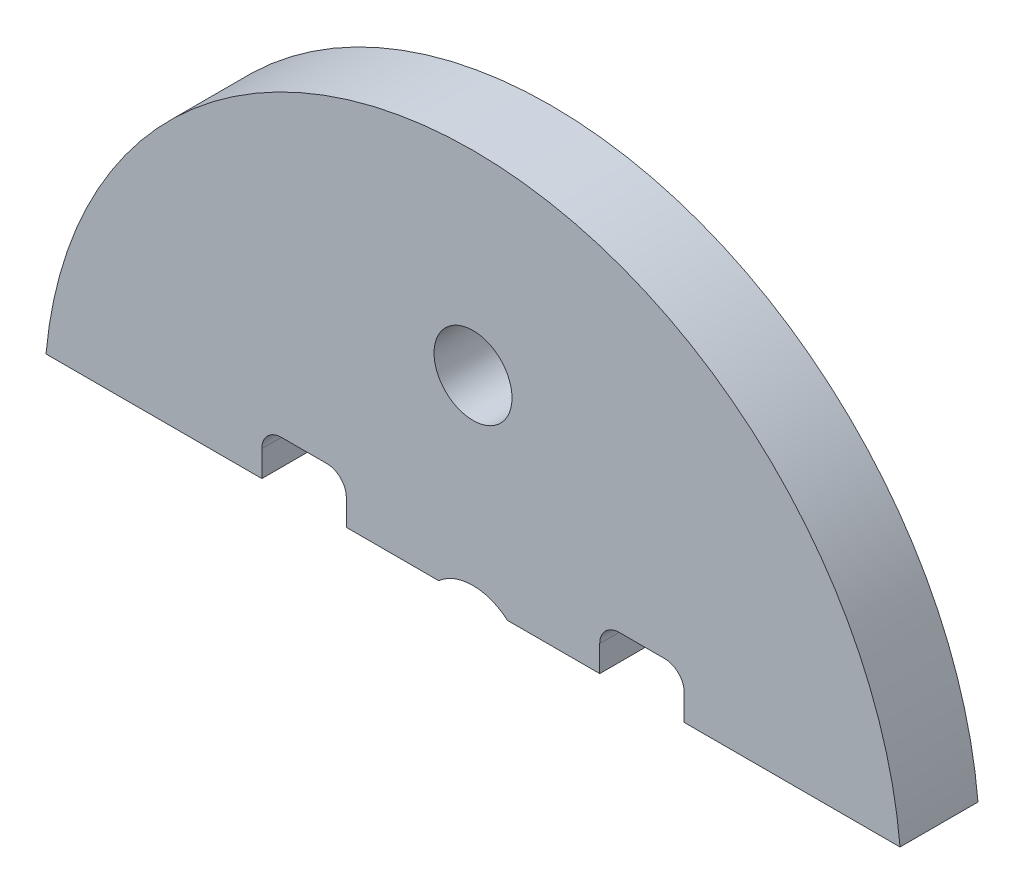
SolidWorks part; units mm, degrees
ref_plane "Alzado" through (0, 0, 0) normal (0, 0, 1) x (1, 0, 0)
ref_plane "Planta" through (0, 0, 0) normal (0, 1, 0) x (1, 0, 0)
ref_plane "Vista lateral" through (0, 0, 0) normal (1, 0, 0) x (0, 0, -1)
sketch "Model" plane through (0, 0, 0) normal (0, 0, 1) x (1, 0, 0)
  line L0 (223.1228, 245.202) -> (221.3728, 245.202)
  line L1 (208.3728, 245.202) -> (210.1228, 245.202)
  line L2 (223.8728, 243.452) -> (232.1795, 243.452)
  line L3 (223.8728, 243.452) -> (223.8728, 244.452)
  line L4 (220.6228, 244.452) -> (220.6228, 243.452)
  line L5 (210.8728, 244.452) -> (210.8728, 243.452)
  line L6 (207.6228, 243.452) -> (207.6228, 244.452)
  line L7 (199.3161, 243.452) -> (207.6228, 243.452)
  line L8 (210.8728, 243.452) -> (214.4249, 243.452)
  line L9 (217.0707, 243.452) -> (220.6228, 243.452)
  circle A0 centre (215.7478, 250.952) radius 1.5
  arc A1 (221.3728, 245.202) -> (220.6228, 244.452) centre (221.3728, 244.452) ccw
  arc A2 (223.8728, 244.452) -> (223.1228, 245.202) centre (223.1228, 244.452) ccw
  arc A3 (210.8728, 244.452) -> (210.1228, 245.202) centre (210.1228, 244.452) ccw
  arc A4 (208.3728, 245.202) -> (207.6228, 244.452) centre (208.3728, 244.452) ccw
  arc A5 (217.0707, 243.452) -> (214.4249, 243.452) centre (215.7478, 241.952) ccw
  arc A6 (232.1795, 243.452) -> (199.3161, 243.452) centre (215.7478, 241.952) ccw
extrude "Saliente-Extruir1" add sketch "Model" along normal blind 3
